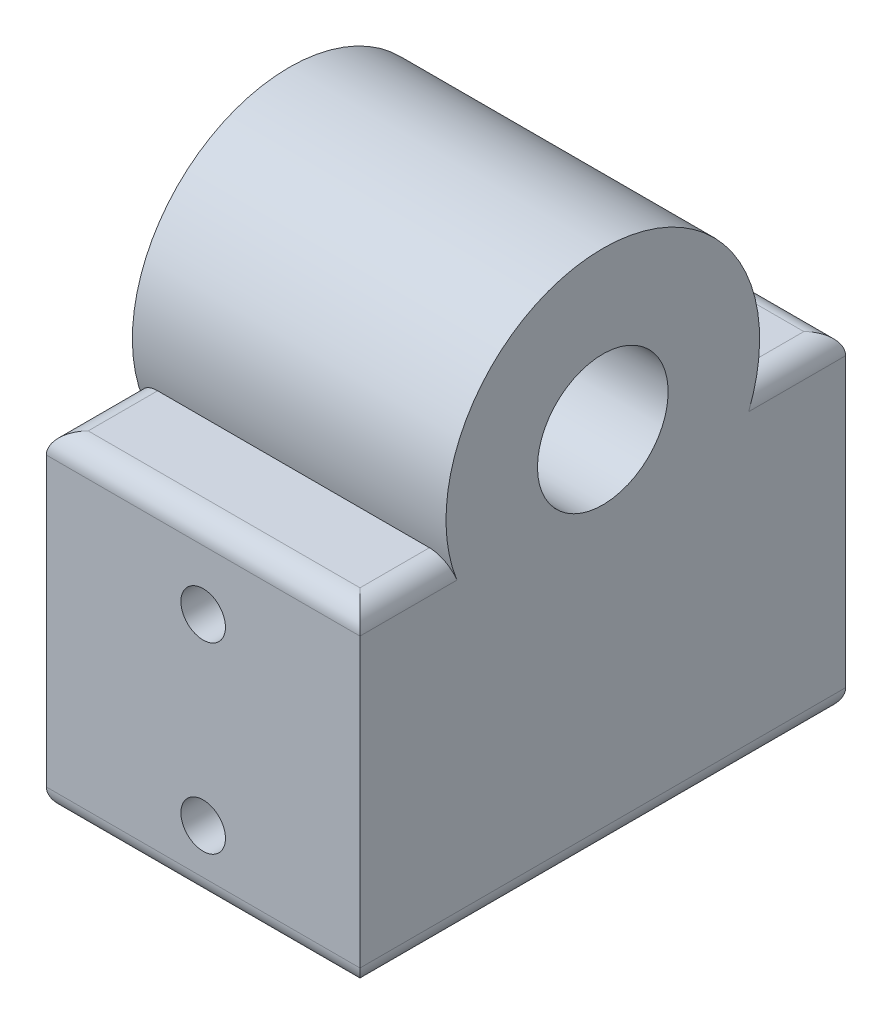
SolidWorks part; units mm, degrees
material "6061 Alloy"
ref_plane "Front Plane" through (0, 0, 0) normal (0, 0, 1) x (1, 0, 0)
ref_plane "Top Plane" through (0, 0, 0) normal (0, 1, 0) x (1, 0, 0)
ref_plane "Right Plane" through (0, 0, 0) normal (1, 0, 0) x (0, 0, -1)
sketch "Sketch1" plane through (0, 0, 0) normal (0, 1, 0) x (1, 0, 0)
  line L1 (-9.525, -14.75) -> (9.525, -14.75)
  line L2 (-9.525, -14.75) -> (-9.525, 14.75)
  line L3 (-9.525, 14.75) -> (9.525, 14.75)
  line L4 (9.525, -14.75) -> (9.525, 14.75)
  line L5 (-9.525, -14.75) -> (9.525, 14.75) construction
  line L6 (-9.525, 14.75) -> (9.525, -14.75) construction
  point P0 (0, 0)
  dimension "D1" = 19.05
  dimension "D2" = 29.5
extrude "Body" add sketch "Sketch1" against normal blind 31.75
sketch "Sketch8" plane through (-9.525, 0, 0) normal (-1, 0, 0) x (0, 0, 1)
  line L0 (0, 0) -> (0, -9.525) construction
  line L1 (-14.75, 0) -> (14.75, 0) construction
  circle A1 centre (0, -9.525) radius 3.9688
  dimension "D1" = 7.9375
  dimension "D2" = 9.525
extrude "Axle Hole" cut sketch "Sketch8" against normal through all
hole_wizard "#6-32 Tapped Hole1" positions "3DSketch1" profile "Sketch9" tap size "#6-32" standard "Ansi Inch" end condition through all
sketch3d "3DSketch1"
  line L6 (0, -31.75, 14.75) -> (0, 0, 14.75) construction
  line L8 (-9.525, -27.75, 14.75) -> (9.525, -27.75, 14.75) construction
  line L9 (-9.525, -31.75, 14.75) -> (-9.525, 0, 14.75) construction
  line L10 (9.525, -31.75, 14.75) -> (9.525, 0, 14.75) construction
  line L11 (-9.525, -16.6375, 14.75) -> (9.525, -16.6375, 14.75) construction
  line L12 (-9.525, -31.75, 14.75) -> (9.525, -31.75, 14.75) construction
  line L14 (-9.525, 0, 14.75) -> (9.525, 0, 14.75) construction
  point P4 (0, -27.75, 14.75)
  point P6 (0, -16.6375, 14.75)
  dimension "D3" = 4
  dimension "D4" = 11.1125
cosmetic thread "Hole Thread1" parameters "D2"=3.5052
cosmetic thread "Hole Thread2" parameters "D2"=3.5052
sketch "Sketch9" plane through (0, -27.75, 14.75) normal (1, 0, 0) x (0, -1, 0)
  line L0 (0, 0) -> (0, 29.5)
  line L1 (0, 29.5) -> (1.3525, 29.5)
  line L2 (1.3525, 29.5) -> (1.3525, 0)
  line L5 (1.3525, 0) -> (0, 0)
  line L11 (0, -6.35) -> (0, 107.95) construction
  dimension "Thru Tap Drill Dia." = 2.7051
  dimension "Thru Tap Drill Depth" = 29.5
sketch "Sketch10" plane through (9.525, 0, 0) normal (1, 0, 0) x (0, 0, -1)
  line L3 (-14.75, -11.75) -> (14.75, -11.75)
  line L4 (-14.75, -31.75) -> (-14.75, 0) construction
  line L5 (14.75, -31.75) -> (14.75, 0) construction
  line L7 (-14.75, -31.75) -> (14.75, -31.75) construction
  circle A0 centre (0, -9.525) radius 3.9688 construction
  circle A1 centre (0, -9.525) radius 9.525
  dimension "D1" = 20
  dimension "D2" = 19.05
extrude "Round Over" cut sketch "Sketch10" against normal through all
fillet "Fillet1" radius 1.27 10 edges at (-9.525, -31.75, 0) (0, -31.75, -14.75) (0, -31.75, 14.75) (9.525, -31.75, 0) (0, -11.75, -14.75) (-9.525, -11.75, -12.0057) (0, -11.75, 14.75) (-9.525, -11.75, 12.0057) (9.525, -11.75, -12.0057) (9.525, -11.75, 12.0057)
